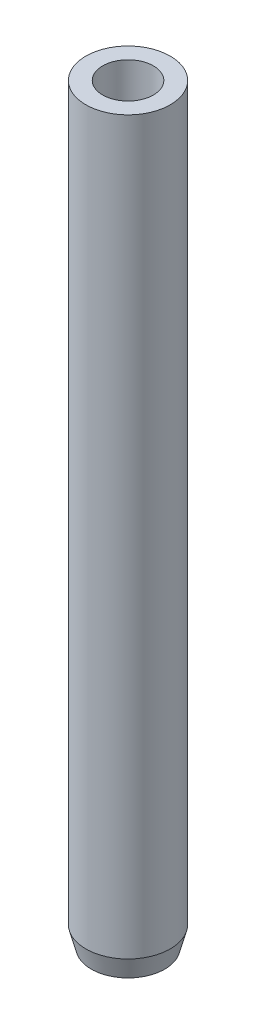
SolidWorks part; units mm, degrees
ref_plane "Front Plane" through (0, 0, 0) normal (0, 0, 1) x (1, 0, 0)
ref_plane "Top Plane" through (0, 0, 0) normal (0, 1, 0) x (1, 0, 0)
ref_plane "Right Plane" through (0, 0, 0) normal (1, 0, 0) x (0, 0, -1)
sketch "Sketch1" plane through (0, 0, 0) normal (0, 0, 1) x (1, 0, 0)
  line L0 (0, 0) -> (0, 38.5)
  line L1 (0, 38.5) -> (-1.5, 38.5)
  line L2 (-1.5, 38.5) -> (-1.5, 44.5)
  line L3 (-1.5, 44.5) -> (-2.5, 44.5)
  line L4 (-2.5, 44.5) -> (-2.5, 1.2)
  line L5 (-2.5, 1.2) -> (-2.1785, 0)
  line L6 (-2.1785, 0) -> (0, 0) construction
  line L7 (0, 0) -> (0, 44.5) construction
  line L8 (0, 0) -> (0, -0.5)
  arc A0 (0, -0.5) -> (-2.1785, 0) centre (0, 4.4957) cw
  point P13 (-0.016, -0.5759)
  dimension "D8" = 4.9957
  dimension "D1" = 5
  dimension "D2" = 3
  dimension "D3" = 6
  dimension "D4" = 45
  dimension "D5" = 15
  dimension "D6" = 1.7
  dimension "D7" = 0.5
revolve "Revolve1" add sketch "Sketch1" angle 360 about L7
ref_plane "Plane1" through (0, -0.5, 0) normal (0, -1, 0) x (-1, 0, 0)
